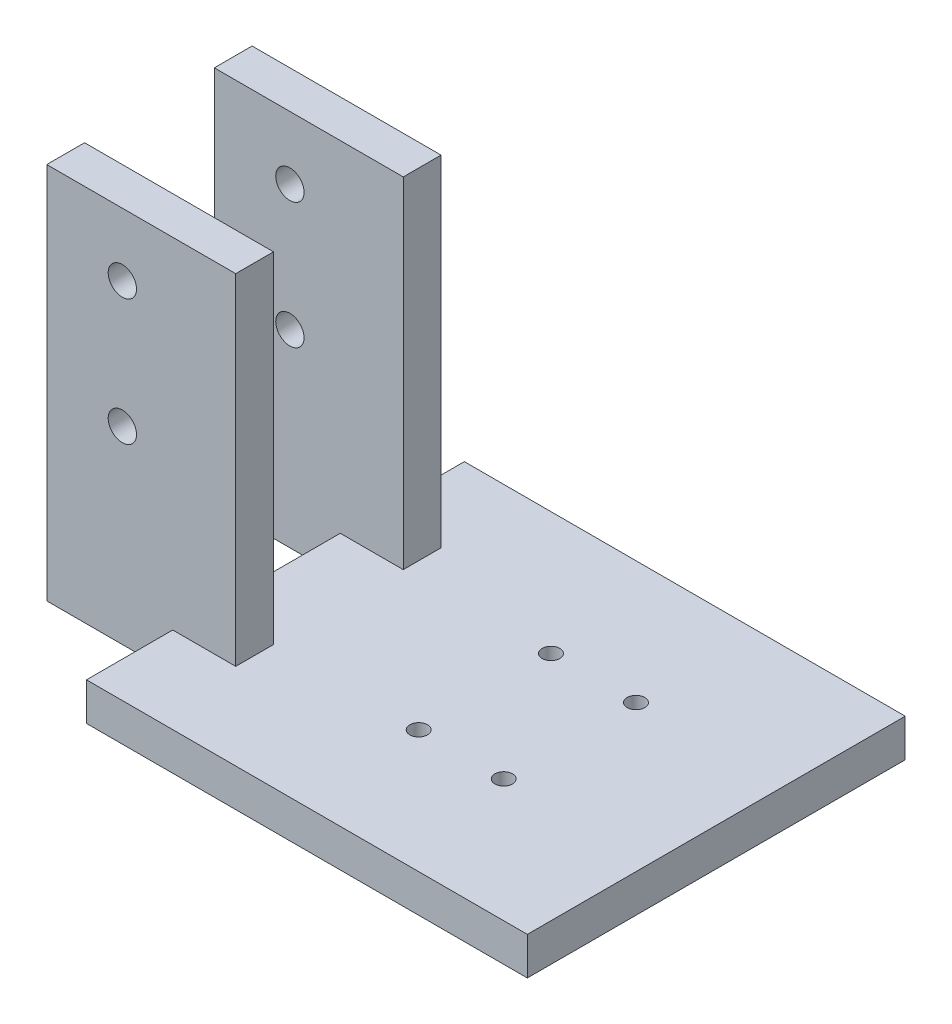
SolidWorks part; units mm, degrees
ref_plane "前视基准面" through (0, 0, 0) normal (0, 0, 1) x (1, 0, 0)
ref_plane "上视基准面" through (0, 0, 0) normal (0, 1, 0) x (1, 0, 0)
ref_plane "右视基准面" through (0, 0, 0) normal (1, 0, 0) x (0, 0, -1)
other "Configuration Table"
sketch "草图1" plane through (0, 0, 0) normal (0, 0, 1) x (1, 0, 0)
  line L1 (20, -40) -> (90, -40)
  line L2 (20, -40) -> (20, -34)
  line L3 (20, -34) -> (90, -34)
  line L4 (90, -40) -> (90, -34)
extrude "相机背面托板" add sketch "草图1" along normal blind 60 from offset 30
sketch "草图2" plane through (0, 0, 0) normal (0, 0, 1) x (1, 0, 0)
  line L1 (0, -40) -> (30, -40)
  line L2 (0, -40) -> (0, 20)
  line L3 (0, 20) -> (30, 20)
  line L4 (30, -40) -> (30, 20)
extrude "夹臂侧板-16.3" add sketch "草图2" along normal blind 6 from offset 16.3
sketch "草图3" plane through (0, 0, 0) normal (0, 0, 1) x (1, 0, 0)
  line L1 (0, -40) -> (30, -40)
  line L2 (0, -40) -> (0, 20)
  line L3 (0, 20) -> (30, 20)
  line L4 (30, -40) -> (30, 20)
extrude "夹臂侧板10.3" add sketch "草图3" along normal blind 6 from offset 10.3
sketch "草图4" plane through (0, 0, 0) normal (0, 0, 1) x (1, 0, 0)
  circle A0 centre (12, -10) radius 2.25
  circle A1 centre (12, 10) radius 2.25
extrude "夹臂M4通孔" cut sketch "草图4" against normal through all and the other way through all
sketch "草图5" plane through (0, 0, 0) normal (0, 1, 0) x (1, 0, 0)
  circle A0 centre (53.25, -10.5) radius 2.7
  circle A1 centre (53.25, 10.5) radius 2.7
  circle A2 centre (66.75, -10.5) radius 2.7
  circle A3 centre (66.75, 10.5) radius 2.7
extrude "相机6mm绝缘支柱" add sketch "草图5" along normal blind 6 from offset 46
sketch "草图6" plane through (0, 0, 0) normal (0, 1, 0) x (1, 0, 0)
  circle A0 centre (53.25, -10.5) radius 1.4
  circle A1 centre (53.25, 10.5) radius 1.4
  circle A2 centre (66.75, -10.5) radius 1.4
  circle A3 centre (66.75, 10.5) radius 1.4
extrude "21x13p5相机孔阵" cut sketch "草图6" against normal through all and the other way through all
